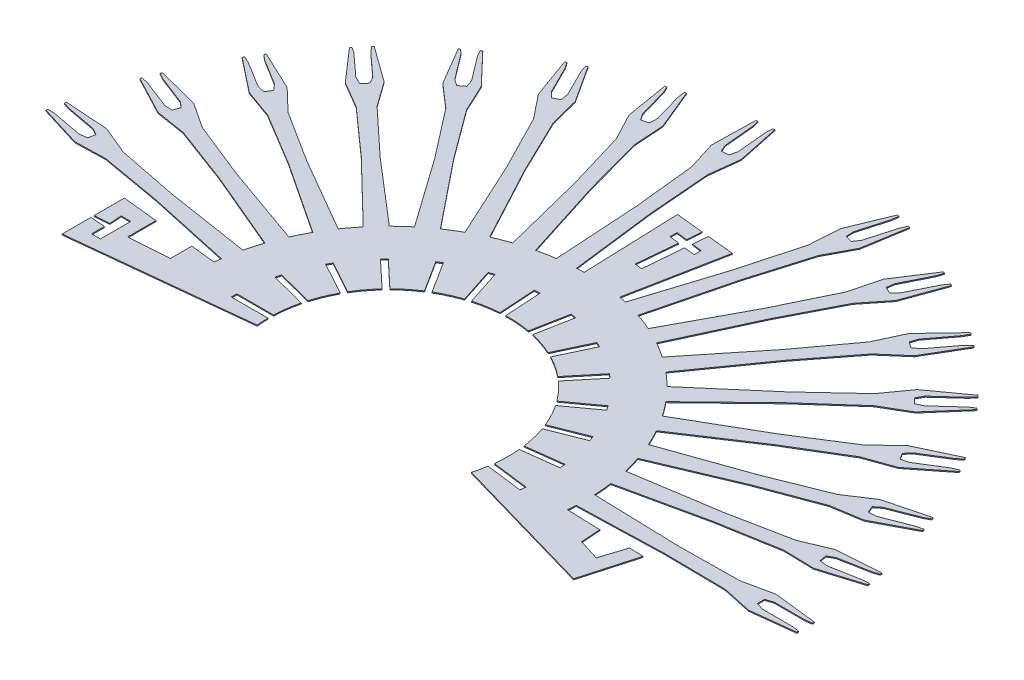
SolidWorks part; units mm, degrees
ref_plane "Front Plane" through (0, 0, 0) normal (0, 0, 1) x (1, 0, 0)
ref_plane "Top Plane" through (0, 0, 0) normal (0, 1, 0) x (1, 0, 0)
ref_plane "Right Plane" through (0, 0, 0) normal (1, 0, 0) x (0, 0, -1)
sketch "Sketch1" plane through (0, 0, 0) normal (0, 1, 0) x (1, 0, 0)
  line L5558 (72.849, 49.9) -> (72.743, 47.748) construction
  line L5559 (72.743, 47.748) -> (72.425, 45.667) construction
  line L5560 (72.425, 45.667) -> (71.896, 43.656) construction
  line L5561 (71.896, 43.656) -> (71.208, 41.716) construction
  line L5562 (71.208, 41.716) -> (70.309, 39.899) construction
  line L5563 (70.309, 39.899) -> (69.286, 38.171) construction
  line L5564 (69.286, 38.171) -> (66.71, 35.048) construction
  line L5565 (66.71, 35.048) -> (63.588, 32.491) construction
  line L5566 (63.588, 32.491) -> (61.877, 31.45) construction
  line L5567 (61.877, 31.45) -> (60.043, 30.551) construction
  line L5568 (60.043, 30.551) -> (58.12, 29.863) construction
  line L5569 (58.12, 29.863) -> (56.109, 29.333) construction
  line L5570 (56.109, 29.333) -> (54.01, 29.016) construction
  line L5571 (54.01, 29.016) -> (51.876, 28.91) construction
  line L5572 (51.876, 28.91) -> (49.724, 29.016) construction
  line L5573 (49.724, 29.016) -> (47.643, 29.333) construction
  line L5574 (47.643, 29.333) -> (45.632, 29.863) construction
  line L5575 (45.632, 29.863) -> (43.692, 30.551) construction
  line L5576 (43.692, 30.551) -> (41.839, 31.45) construction
  line L5577 (41.839, 31.45) -> (40.128, 32.491) construction
  line L5578 (40.128, 32.491) -> (37.006, 35.048) construction
  line L5579 (37.006, 35.048) -> (34.431, 38.171) construction
  line L5580 (34.431, 38.171) -> (33.408, 39.899) construction
  line L5581 (33.408, 39.899) -> (32.508, 41.716) construction
  line L5582 (32.508, 41.716) -> (31.821, 43.656) construction
  line L5583 (31.821, 43.656) -> (31.291, 45.667) construction
  line L5584 (31.291, 45.667) -> (30.974, 47.748) construction
  line L5585 (30.974, 47.748) -> (30.868, 49.9) construction
  line L5586 (30.868, 49.9) -> (30.974, 52.035) construction
  line L5587 (30.974, 52.035) -> (31.291, 54.134) construction
  line L5588 (31.291, 54.134) -> (31.821, 56.145) construction
  line L5589 (31.821, 56.145) -> (32.508, 58.067) construction
  line L5590 (32.508, 58.067) -> (33.408, 59.919) construction
  line L5591 (33.408, 59.919) -> (34.431, 61.648) construction
  line L5592 (34.431, 61.648) -> (37.006, 64.77) construction
  line L5593 (37.006, 64.77) -> (40.128, 67.328) construction
  line L5594 (40.128, 67.328) -> (41.839, 68.368) construction
  line L5595 (41.839, 68.368) -> (43.692, 69.268) construction
  line L5596 (43.692, 69.268) -> (45.632, 69.956) construction
  line L5597 (45.632, 69.956) -> (47.643, 70.485) construction
  line L5598 (47.643, 70.485) -> (49.724, 70.803) construction
  line L5599 (49.724, 70.803) -> (51.876, 70.908) construction
  line L5600 (51.876, 70.908) -> (54.01, 70.803) construction
  line L5601 (54.01, 70.803) -> (56.109, 70.485) construction
  line L5602 (56.109, 70.485) -> (58.12, 69.956) construction
  line L5603 (58.12, 69.956) -> (60.043, 69.268) construction
  line L5604 (60.043, 69.268) -> (61.877, 68.368) construction
  line L5605 (61.877, 68.368) -> (63.588, 67.328) construction
  line L5606 (63.588, 67.328) -> (66.71, 64.77) construction
  line L5607 (66.71, 64.77) -> (69.286, 61.648) construction
  line L5608 (69.286, 61.648) -> (70.309, 59.919) construction
  line L5609 (70.309, 59.919) -> (71.208, 58.067) construction
  line L5610 (71.208, 58.067) -> (71.896, 56.145) construction
  line L5611 (71.896, 56.145) -> (72.425, 54.134) construction
  line L5612 (72.425, 54.134) -> (72.743, 52.035) construction
  line L5613 (72.743, 52.035) -> (72.849, 49.9) construction
  line L5614 (62.054, 49.9) -> (61.842, 47.854) construction
  line L5615 (61.842, 47.854) -> (61.26, 45.932) construction
  line L5616 (61.26, 45.932) -> (60.307, 44.203) construction
  line L5617 (60.307, 44.203) -> (59.055, 42.704) construction
  line L5618 (59.055, 42.704) -> (57.556, 41.451) construction
  line L5619 (57.556, 41.451) -> (55.827, 40.499) construction
  line L5620 (55.827, 40.499) -> (53.922, 39.917) construction
  line L5621 (53.922, 39.917) -> (51.858, 39.705) construction
  line L5622 (51.858, 39.705) -> (49.795, 39.917) construction
  line L5623 (49.795, 39.917) -> (47.89, 40.499) construction
  line L5624 (47.89, 40.499) -> (46.143, 41.451) construction
  line L5625 (46.143, 41.451) -> (44.644, 42.704) construction
  line L5626 (44.644, 42.704) -> (43.392, 44.203) construction
  line L5627 (43.392, 44.203) -> (42.439, 45.932) construction
  line L5628 (42.439, 45.932) -> (41.857, 47.854) construction
  line L5629 (41.857, 47.854) -> (41.645, 49.9) construction
  line L5630 (41.645, 49.9) -> (41.857, 51.964) construction
  line L5631 (41.857, 51.964) -> (42.439, 53.869) construction
  line L5632 (42.439, 53.869) -> (43.392, 55.615) construction
  line L5633 (43.392, 55.615) -> (44.644, 57.115) construction
  line L5634 (44.644, 57.115) -> (46.143, 58.367) construction
  line L5635 (46.143, 58.367) -> (47.89, 59.32) construction
  line L5636 (47.89, 59.32) -> (49.795, 59.902) construction
  line L5637 (49.795, 59.902) -> (51.858, 60.113) construction
  line L5638 (51.858, 60.113) -> (53.922, 59.902) construction
  line L5639 (53.922, 59.902) -> (55.827, 59.32) construction
  line L5640 (55.827, 59.32) -> (57.556, 58.367) construction
  line L5641 (57.556, 58.367) -> (59.055, 57.115) construction
  line L5642 (59.055, 57.115) -> (60.307, 55.615) construction
  line L5643 (60.307, 55.615) -> (61.26, 53.869) construction
  line L5644 (61.26, 53.869) -> (61.842, 51.964) construction
  line L5645 (61.842, 51.964) -> (62.054, 49.9) construction
  line L5646 (30.85, 49.9) -> (51.841, 49.9) construction
  line L5647 (53.675, 70.82) -> (51.841, 49.9) construction
  line L5648 (72.531, 46.249) -> (51.858, 49.9) construction
  line L5649 (72.796, 48.436) -> (51.841, 49.9) construction
  line L5650 (51.488, 70.891) -> (51.841, 49.9) construction
  line L5651 (55.862, 70.52) -> (51.858, 49.9) construction
  line L5652 (30.956, 47.696) -> (51.841, 49.9) construction
  line L5653 (30.956, 52.088) -> (51.841, 49.9) construction
  line L5654 (72.037, 44.115) -> (51.841, 49.9) construction
  line L5655 (62.406, 49.177) -> (67.045, 49.424) construction
  line L5656 (67.345, 50.077) -> (67.469, 50.324) construction
  line L5657 (67.469, 50.324) -> (67.68, 50.377) construction
  line L5658 (67.68, 50.377) -> (67.892, 50.271) construction
  line L5659 (67.892, 50.271) -> (67.945, 50.059) construction
  line L5660 (67.945, 50.059) -> (67.839, 49.848) construction
  line L5661 (67.839, 49.848) -> (67.628, 49.759) construction
  line L5662 (67.628, 49.759) -> (67.416, 49.865) construction
  line L5663 (67.416, 49.865) -> (67.345, 50.077) construction
  line L5664 (69.832, 50.094) -> (69.938, 50.341) construction
  line L5665 (69.938, 50.341) -> (70.168, 50.394) construction
  line L5666 (70.168, 50.394) -> (70.379, 50.288) construction
  line L5667 (70.379, 50.288) -> (70.432, 50.077) construction
  line L5668 (70.432, 50.077) -> (70.326, 49.865) construction
  line L5669 (70.326, 49.865) -> (70.115, 49.777) construction
  line L5670 (70.115, 49.777) -> (69.903, 49.883) construction
  line L5671 (69.903, 49.883) -> (69.832, 50.094) construction
  line L5672 (67.045, 49.424) -> (71.702, 49.477) construction
  line L5673 (71.914, 50.094) -> (71.702, 49.477) construction
  line L5674 (62.389, 50.835) -> (67.045, 50.659) construction
  line L5675 (67.045, 50.659) -> (71.702, 50.712) construction
  line L5676 (71.914, 50.094) -> (71.702, 50.712) construction
  line L5677 (70.132, 50.377) -> (67.645, 50.359) construction
  line L5678 (70.15, 49.777) -> (67.645, 49.742) construction
  line L5679 (57.344, 49.953) -> (51.841, 49.9) construction
  line L5680 (62.353, 51.118) -> (66.887, 52.229) construction
  line L5681 (67.045, 52.917) -> (67.345, 53.252) construction
  line L5682 (67.345, 53.252) -> (67.557, 53.199) construction
  line L5683 (67.557, 53.199) -> (67.663, 52.987) construction
  line L5684 (67.663, 52.987) -> (67.61, 52.776) construction
  line L5685 (67.61, 52.776) -> (67.398, 52.652) construction
  line L5686 (67.398, 52.652) -> (67.187, 52.723) construction
  line L5687 (67.187, 52.723) -> (67.045, 52.917) construction
  line L5688 (69.48, 53.393) -> (69.779, 53.746) construction
  line L5689 (69.779, 53.746) -> (69.991, 53.693) construction
  line L5690 (69.991, 53.693) -> (70.097, 53.481) construction
  line L5691 (70.097, 53.481) -> (70.044, 53.269) construction
  line L5692 (70.044, 53.269) -> (69.832, 53.128) construction
  line L5693 (69.832, 53.128) -> (69.621, 53.217) construction
  line L5694 (69.621, 53.217) -> (69.48, 53.393) construction
  line L5695 (66.887, 52.229) -> (71.455, 53.128) construction
  line L5696 (71.543, 53.763) -> (71.455, 53.128) construction
  line L5697 (62.036, 52.758) -> (66.64, 53.428) construction
  line L5698 (66.64, 53.428) -> (71.208, 54.328) construction
  line L5699 (71.543, 53.781) -> (71.208, 54.328) construction
  line L5700 (69.744, 53.728) -> (67.292, 53.252) construction
  line L5701 (69.85, 53.128) -> (67.416, 52.634) construction
  line L5702 (57.238, 50.959) -> (51.841, 49.9) construction
  line L5703 (61.965, 53.023) -> (66.199, 54.945) construction
  line L5704 (66.234, 55.651) -> (66.446, 56.039) construction
  line L5705 (66.446, 56.039) -> (66.693, 56.021) construction
  line L5706 (66.693, 56.021) -> (66.851, 55.827) construction
  line L5707 (66.851, 55.827) -> (66.64, 55.457) construction
  line L5708 (66.64, 55.457) -> (66.393, 55.492) construction
  line L5709 (66.393, 55.492) -> (66.234, 55.651) construction
  line L5710 (68.545, 56.568) -> (68.756, 56.956) construction
  line L5711 (68.756, 56.956) -> (69.003, 56.938) construction
  line L5712 (69.003, 56.938) -> (69.162, 56.744) construction
  line L5713 (69.162, 56.744) -> (68.95, 56.374) construction
  line L5714 (68.95, 56.374) -> (68.703, 56.409) construction
  line L5715 (68.703, 56.409) -> (68.545, 56.568) construction
  line L5716 (66.199, 54.945) -> (70.52, 56.656) construction
  line L5717 (70.503, 57.309) -> (70.52, 56.656) construction
  line L5718 (61.348, 54.575) -> (65.74, 56.092) construction
  line L5719 (65.74, 56.092) -> (70.079, 57.803) construction
  line L5720 (70.503, 57.309) -> (70.079, 57.803) construction
  line L5721 (68.739, 56.938) -> (66.41, 56.021) construction
  line L5722 (68.968, 56.374) -> (66.64, 55.439) construction
  line L5723 (56.956, 51.929) -> (51.841, 49.9) construction
  line L5724 (61.225, 54.822) -> (65.035, 57.485) construction
  line L5725 (64.946, 58.191) -> (65.07, 58.614) construction
  line L5726 (65.07, 58.614) -> (65.317, 58.632) construction
  line L5727 (65.317, 58.632) -> (65.493, 58.473) construction
  line L5728 (65.493, 58.473) -> (65.528, 58.244) construction
  line L5729 (65.528, 58.244) -> (65.37, 58.05) construction
  line L5730 (65.37, 58.05) -> (64.946, 58.191) construction
  line L5731 (67.045, 59.514) -> (67.169, 59.937) construction
  line L5732 (67.169, 59.937) -> (67.416, 59.955) construction
  line L5733 (67.416, 59.955) -> (67.592, 59.796) construction
  line L5734 (67.592, 59.796) -> (67.628, 59.567) construction
  line L5735 (67.628, 59.567) -> (67.469, 59.373) construction
  line L5736 (67.469, 59.373) -> (67.045, 59.514) construction
  line L5737 (65.035, 57.485) -> (68.968, 59.972) construction
  line L5738 (68.827, 60.607) -> (68.968, 59.972) construction
  line L5739 (60.325, 56.233) -> (64.382, 58.526) construction
  line L5740 (64.382, 58.526) -> (68.315, 61.013) construction
  line L5741 (68.827, 60.607) -> (68.315, 61.013) construction
  line L5742 (67.169, 59.919) -> (65.052, 58.579) construction
  line L5743 (67.486, 59.39) -> (65.37, 58.067) construction
  line L5744 (56.497, 52.828) -> (51.858, 49.9) construction
  line L5745 (60.149, 56.444) -> (63.429, 59.761) construction
  line L5746 (63.2, 60.448) -> (63.147, 60.678) construction
  line L5747 (63.147, 60.678) -> (63.288, 60.889) construction
  line L5748 (63.288, 60.889) -> (63.5, 60.942) construction
  line L5749 (63.5, 60.942) -> (63.712, 60.837) construction
  line L5750 (63.712, 60.837) -> (63.765, 60.607) construction
  line L5751 (63.765, 60.607) -> (63.659, 60.396) construction
  line L5752 (63.659, 60.396) -> (63.412, 60.343) construction
  line L5753 (63.412, 60.343) -> (63.2, 60.448) construction
  line L5754 (65.017, 62.124) -> (64.964, 62.371) construction
  line L5755 (64.964, 62.371) -> (65.105, 62.583) construction
  line L5756 (65.105, 62.583) -> (65.317, 62.636) construction
  line L5757 (65.317, 62.636) -> (65.528, 62.53) construction
  line L5758 (65.528, 62.53) -> (65.581, 62.283) construction
  line L5759 (65.581, 62.283) -> (65.476, 62.071) construction
  line L5760 (65.476, 62.071) -> (65.229, 62.018) construction
  line L5761 (65.229, 62.018) -> (65.017, 62.124) construction
  line L5762 (63.429, 59.761) -> (66.834, 62.936) construction
  line L5763 (66.587, 63.535) -> (66.834, 62.936) construction
  line L5764 (59.02, 57.679) -> (62.583, 60.678) construction
  line L5765 (62.583, 60.678) -> (66.005, 63.835) construction
  line L5766 (66.587, 63.535) -> (66.005, 63.835) construction
  line L5767 (65.07, 62.548) -> (63.235, 60.854) construction
  line L5768 (65.493, 62.089) -> (63.659, 60.396) construction
  line L5769 (55.88, 53.622) -> (51.841, 49.9) construction
  line L5770 (58.808, 57.873) -> (61.419, 61.718) construction
  line L5771 (61.083, 62.353) -> (60.995, 62.583) construction
  line L5772 (60.995, 62.583) -> (61.083, 62.794) construction
  line L5773 (61.083, 62.794) -> (61.295, 62.9) construction
  line L5774 (61.295, 62.9) -> (61.507, 62.83) construction
  line L5775 (61.507, 62.83) -> (61.613, 62.618) construction
  line L5776 (61.613, 62.618) -> (61.524, 62.371) construction
  line L5777 (61.524, 62.371) -> (61.313, 62.301) construction
  line L5778 (61.313, 62.301) -> (61.083, 62.353) construction
  line L5779 (62.565, 64.329) -> (62.477, 64.576) construction
  line L5780 (62.477, 64.576) -> (62.565, 64.788) construction
  line L5781 (62.565, 64.788) -> (62.777, 64.893) construction
  line L5782 (62.777, 64.893) -> (62.988, 64.805) construction
  line L5783 (62.988, 64.805) -> (63.094, 64.594) construction
  line L5784 (63.094, 64.594) -> (63.006, 64.364) construction
  line L5785 (63.006, 64.364) -> (62.794, 64.276) construction
  line L5786 (62.794, 64.276) -> (62.565, 64.329) construction
  line L5787 (61.419, 61.718) -> (64.206, 65.458) construction
  line L5788 (63.835, 66.005) -> (64.206, 65.458) construction
  line L5789 (57.485, 58.861) -> (60.431, 62.459) construction
  line L5790 (60.431, 62.459) -> (63.2, 66.199) construction
  line L5791 (63.835, 66.005) -> (63.2, 66.199) construction
  line L5792 (62.53, 64.752) -> (61.031, 62.759) construction
  line L5793 (63.024, 64.382) -> (61.524, 62.389) construction
  line L5794 (55.122, 54.31) -> (51.858, 49.9) construction
  line L5795 (57.238, 59.002) -> (59.09, 63.271) construction
  line L5796 (58.649, 63.835) -> (58.508, 64.047) construction
  line L5797 (58.508, 64.047) -> (58.561, 64.258) construction
  line L5798 (58.561, 64.258) -> (58.755, 64.417) construction
  line L5799 (58.755, 64.417) -> (58.967, 64.364) construction
  line L5800 (58.967, 64.364) -> (59.126, 64.17) construction
  line L5801 (59.126, 64.17) -> (59.073, 63.941) construction
  line L5802 (59.073, 63.941) -> (58.879, 63.8) construction
  line L5803 (58.879, 63.8) -> (58.649, 63.835) construction
  line L5804 (59.743, 66.058) -> (59.602, 66.269) construction
  line L5805 (59.602, 66.269) -> (59.655, 66.481) construction
  line L5806 (59.655, 66.481) -> (59.849, 66.604) construction
  line L5807 (59.849, 66.604) -> (60.06, 66.587) construction
  line L5808 (60.06, 66.587) -> (60.219, 66.393) construction
  line L5809 (60.219, 66.393) -> (60.166, 66.163) construction
  line L5810 (60.166, 66.163) -> (59.972, 66.022) construction
  line L5811 (59.972, 66.022) -> (59.743, 66.058) construction
  line L5812 (59.09, 63.271) -> (61.136, 67.451) construction
  line L5813 (60.695, 67.927) -> (61.136, 67.451) construction
  line L5814 (55.739, 59.743) -> (57.979, 63.818) construction
  line L5815 (57.979, 63.818) -> (60.025, 67.998) construction
  line L5816 (60.678, 67.927) -> (60.025, 67.998) construction
  line L5817 (59.619, 66.463) -> (58.526, 64.223) construction
  line L5818 (60.184, 66.181) -> (59.073, 63.941) construction
  line L5819 (54.257, 54.822) -> (51.841, 49.9) construction
  line L5820 (55.457, 59.849) -> (56.497, 64.382) construction
  line L5821 (55.951, 64.841) -> (55.792, 64.999) construction
  line L5822 (55.792, 64.999) -> (55.792, 65.246) construction
  line L5823 (55.792, 65.246) -> (55.951, 65.423) construction
  line L5824 (55.951, 65.423) -> (56.18, 65.423) construction
  line L5825 (56.18, 65.423) -> (56.339, 65.264) construction
  line L5826 (56.339, 65.264) -> (56.339, 65.035) construction
  line L5827 (56.339, 65.035) -> (56.18, 64.876) construction
  line L5828 (56.18, 64.876) -> (55.951, 64.841) construction
  line L5829 (56.603, 67.239) -> (56.444, 67.398) construction
  line L5830 (56.444, 67.398) -> (56.444, 67.628) construction
  line L5831 (56.444, 67.628) -> (56.603, 67.822) construction
  line L5832 (56.603, 67.822) -> (56.85, 67.822) construction
  line L5833 (56.85, 67.822) -> (57.009, 67.663) construction
  line L5834 (57.009, 67.663) -> (57.009, 67.416) construction
  line L5835 (57.009, 67.416) -> (56.85, 67.257) construction
  line L5836 (56.85, 67.257) -> (56.603, 67.239) construction
  line L5837 (56.497, 64.382) -> (57.732, 68.88) construction
  line L5838 (57.203, 69.25) -> (57.732, 68.88) construction
  line L5839 (53.852, 60.29) -> (55.298, 64.717) construction
  line L5840 (55.298, 64.717) -> (56.533, 69.197) construction
  line L5841 (57.185, 69.25) -> (56.533, 69.197) construction
  line L5842 (56.427, 67.61) -> (55.757, 65.211) construction
  line L5843 (57.009, 67.451) -> (56.356, 65.035) construction
  line L5844 (53.305, 55.192) -> (51.841, 49.9) construction
  line L5845 (51.664, 60.484) -> (50.994, 65.088) construction
  line L5846 (50.324, 65.317) -> (50.112, 65.423) construction
  line L5847 (50.112, 65.423) -> (50.024, 65.634) construction
  line L5848 (50.024, 65.634) -> (50.112, 65.846) construction
  line L5849 (50.112, 65.846) -> (50.324, 65.952) construction
  line L5850 (50.324, 65.952) -> (50.553, 65.846) construction
  line L5851 (50.553, 65.846) -> (50.641, 65.634) construction
  line L5852 (50.641, 65.634) -> (50.553, 65.423) construction
  line L5853 (50.553, 65.423) -> (50.324, 65.317) construction
  line L5854 (50.077, 67.786) -> (49.865, 67.892) construction
  line L5855 (49.865, 67.892) -> (49.795, 68.104) construction
  line L5856 (49.795, 68.104) -> (49.865, 68.315) construction
  line L5857 (49.865, 68.315) -> (50.077, 68.421) construction
  line L5858 (50.077, 68.421) -> (50.324, 68.315) construction
  line L5859 (50.324, 68.315) -> (50.394, 68.104) construction
  line L5860 (50.394, 68.104) -> (50.324, 67.892) construction
  line L5861 (50.324, 67.892) -> (50.077, 67.786) construction
  line L5862 (50.994, 65.088) -> (50.535, 69.727) construction
  line L5863 (49.918, 69.885) -> (50.535, 69.727) construction
  line L5864 (50.006, 60.325) -> (49.759, 64.964) construction
  line L5865 (49.759, 64.964) -> (49.318, 69.603) construction
  line L5866 (49.9, 69.885) -> (49.318, 69.603) construction
  line L5867 (49.777, 68.068) -> (50.024, 65.599) construction
  line L5868 (50.377, 68.139) -> (50.624, 65.652) construction
  line L5869 (51.312, 55.368) -> (51.858, 49.9) construction
  line L5870 (49.724, 60.272) -> (48.225, 64.664) construction
  line L5871 (47.519, 64.788) -> (47.308, 64.841) construction
  line L5872 (47.308, 64.841) -> (47.184, 65.052) construction
  line L5873 (47.184, 65.052) -> (47.237, 65.264) construction
  line L5874 (47.237, 65.264) -> (47.413, 65.387) construction
  line L5875 (47.413, 65.387) -> (47.66, 65.334) construction
  line L5876 (47.66, 65.334) -> (47.784, 65.158) construction
  line L5877 (47.784, 65.158) -> (47.731, 64.946) construction
  line L5878 (47.731, 64.946) -> (47.519, 64.788) construction
  line L5879 (46.831, 67.169) -> (46.62, 67.222) construction
  line L5880 (46.62, 67.222) -> (46.496, 67.433) construction
  line L5881 (46.496, 67.433) -> (46.549, 67.645) construction
  line L5882 (46.549, 67.645) -> (46.725, 67.769) construction
  line L5883 (46.725, 67.769) -> (46.972, 67.716) construction
  line L5884 (46.972, 67.716) -> (47.096, 67.539) construction
  line L5885 (47.096, 67.539) -> (47.043, 67.328) construction
  line L5886 (47.043, 67.328) -> (46.831, 67.169) construction
  line L5887 (48.225, 64.664) -> (46.937, 69.144) construction
  line L5888 (46.284, 69.18) -> (46.937, 69.144) construction
  line L5889 (48.119, 59.796) -> (47.043, 64.329) construction
  line L5890 (47.043, 64.329) -> (45.738, 68.809) construction
  line L5891 (46.267, 69.18) -> (45.738, 68.792) construction
  line L5892 (46.478, 67.381) -> (47.166, 64.982) construction
  line L5893 (47.061, 67.557) -> (47.766, 65.158) construction
  line L5894 (50.324, 55.174) -> (51.841, 49.9) construction
  line L5895 (47.854, 59.708) -> (45.579, 63.747) construction
  line L5896 (44.873, 63.729) -> (44.662, 63.765) construction
  line L5897 (44.662, 63.765) -> (44.503, 63.923) construction
  line L5898 (44.503, 63.923) -> (44.503, 64.153) construction
  line L5899 (44.503, 64.153) -> (44.662, 64.311) construction
  line L5900 (44.662, 64.311) -> (44.891, 64.311) construction
  line L5901 (44.891, 64.311) -> (45.05, 64.135) construction
  line L5902 (45.05, 64.135) -> (45.05, 63.923) construction
  line L5903 (45.05, 63.923) -> (44.873, 63.729) construction
  line L5904 (43.762, 65.952) -> (43.55, 65.969) construction
  line L5905 (43.55, 65.969) -> (43.356, 66.128) construction
  line L5906 (43.356, 66.128) -> (43.392, 66.375) construction
  line L5907 (43.392, 66.375) -> (43.55, 66.534) construction
  line L5908 (43.55, 66.534) -> (43.78, 66.534) construction
  line L5909 (43.78, 66.534) -> (43.938, 66.34) construction
  line L5910 (43.938, 66.34) -> (43.938, 66.128) construction
  line L5911 (43.938, 66.128) -> (43.762, 65.952) construction
  line L5912 (45.579, 63.747) -> (43.498, 67.91) construction
  line L5913 (42.845, 67.839) -> (43.498, 67.91) construction
  line L5914 (46.373, 58.949) -> (44.485, 63.2) construction
  line L5915 (44.485, 63.2) -> (42.386, 67.363) construction
  line L5916 (42.827, 67.839) -> (42.386, 67.363) construction
  line L5917 (43.374, 66.111) -> (44.485, 63.87) construction
  line L5918 (43.921, 66.393) -> (45.032, 64.153) construction
  line L5919 (49.389, 54.804) -> (51.841, 49.9) construction
  line L5920 (46.126, 58.808) -> (43.145, 62.371) construction
  line L5921 (42.457, 62.23) -> (42.245, 62.195) construction
  line L5922 (42.245, 62.195) -> (42.051, 62.336) construction
  line L5923 (42.051, 62.336) -> (41.998, 62.565) construction
  line L5924 (41.998, 62.565) -> (42.139, 62.759) construction
  line L5925 (42.139, 62.759) -> (42.369, 62.777) construction
  line L5926 (42.369, 62.777) -> (42.563, 62.653) construction
  line L5927 (42.563, 62.653) -> (42.58, 62.442) construction
  line L5928 (42.58, 62.442) -> (42.457, 62.23) construction
  line L5929 (40.958, 64.188) -> (40.746, 64.17) construction
  line L5930 (40.746, 64.17) -> (40.552, 64.294) construction
  line L5931 (40.552, 64.294) -> (40.499, 64.541) construction
  line L5932 (40.499, 64.541) -> (40.64, 64.717) construction
  line L5933 (40.64, 64.717) -> (40.869, 64.752) construction
  line L5934 (40.869, 64.752) -> (41.063, 64.611) construction
  line L5935 (41.063, 64.611) -> (41.081, 64.4) construction
  line L5936 (41.081, 64.4) -> (40.958, 64.188) construction
  line L5937 (43.145, 62.371) -> (40.323, 66.075) construction
  line L5938 (39.705, 65.881) -> (40.323, 66.075) construction
  line L5939 (44.803, 57.803) -> (42.157, 61.63) construction
  line L5940 (42.157, 61.63) -> (39.352, 65.334) construction
  line L5941 (39.705, 65.881) -> (39.352, 65.334) construction
  line L5942 (40.534, 64.276) -> (42.051, 62.301) construction
  line L5943 (41.028, 64.647) -> (42.545, 62.671) construction
  line L5944 (48.525, 54.275) -> (51.858, 49.9) construction
  line L5945 (44.591, 57.609) -> (41.01, 60.572) construction
  line L5946 (40.358, 60.29) -> (40.146, 60.219) construction
  line L5947 (40.146, 60.219) -> (39.934, 60.325) construction
  line L5948 (39.934, 60.325) -> (39.846, 60.537) construction
  line L5949 (39.846, 60.537) -> (39.952, 60.748) construction
  line L5950 (39.952, 60.748) -> (40.164, 60.819) construction
  line L5951 (40.164, 60.819) -> (40.375, 60.748) construction
  line L5952 (40.375, 60.748) -> (40.464, 60.537) construction
  line L5953 (40.464, 60.537) -> (40.358, 60.29) construction
  line L5954 (38.523, 61.965) -> (38.312, 61.877) construction
  line L5955 (38.312, 61.877) -> (38.1, 61.983) construction
  line L5956 (38.1, 61.983) -> (38.012, 62.195) construction
  line L5957 (38.012, 62.195) -> (38.118, 62.406) construction
  line L5958 (38.118, 62.406) -> (38.329, 62.495) construction
  line L5959 (38.329, 62.495) -> (38.541, 62.406) construction
  line L5960 (38.541, 62.406) -> (38.629, 62.195) construction
  line L5961 (38.629, 62.195) -> (38.523, 61.965) construction
  line L5962 (41.01, 60.572) -> (37.553, 63.694) construction
  line L5963 (36.989, 63.394) -> (37.553, 63.694) construction
  line L5964 (43.48, 56.374) -> (40.181, 59.655) construction
  line L5965 (40.181, 59.655) -> (36.724, 62.777) construction
  line L5966 (36.971, 63.377) -> (36.724, 62.777) construction
  line L5967 (38.1, 61.965) -> (39.952, 60.29) construction
  line L5968 (38.506, 62.424) -> (40.358, 60.748) construction
  line L5969 (47.784, 53.587) -> (51.841, 49.9) construction
  line L5970 (43.303, 56.145) -> (39.247, 58.402) construction
  line L5971 (38.647, 58.014) -> (38.453, 57.908) construction
  line L5972 (38.453, 57.908) -> (38.223, 57.961) construction
  line L5973 (38.223, 57.961) -> (38.118, 58.173) construction
  line L5974 (38.118, 58.173) -> (38.171, 58.385) construction
  line L5975 (38.171, 58.385) -> (38.594, 58.455) construction
  line L5976 (38.594, 58.455) -> (38.7, 58.244) construction
  line L5977 (38.7, 58.244) -> (38.647, 58.014) construction
  line L5978 (36.53, 59.32) -> (36.354, 59.214) construction
  line L5979 (36.354, 59.214) -> (36.107, 59.267) construction
  line L5980 (36.107, 59.267) -> (36.001, 59.478) construction
  line L5981 (36.001, 59.478) -> (36.054, 59.69) construction
  line L5982 (36.054, 59.69) -> (36.477, 59.761) construction
  line L5983 (36.477, 59.761) -> (36.583, 59.549) construction
  line L5984 (36.583, 59.549) -> (36.53, 59.32) construction
  line L5985 (39.247, 58.402) -> (35.278, 60.854) construction
  line L5986 (34.766, 60.448) -> (35.278, 60.837) construction
  line L5987 (42.439, 54.733) -> (38.594, 57.344) construction
  line L5988 (38.594, 57.344) -> (34.625, 59.796) construction
  line L5989 (34.766, 60.431) -> (34.625, 59.796) construction
  line L5990 (36.124, 59.249) -> (38.241, 57.926) construction
  line L5991 (36.442, 59.761) -> (38.559, 58.455) construction
  line L5992 (47.184, 52.776) -> (51.841, 49.9) construction
  line L5993 (42.316, 54.469) -> (37.888, 55.951) construction
  line L5994 (37.377, 55.457) -> (37.218, 55.316) construction
  line L5995 (37.218, 55.316) -> (36.989, 55.316) construction
  line L5996 (36.989, 55.316) -> (36.83, 55.51) construction
  line L5997 (36.83, 55.51) -> (36.848, 55.739) construction
  line L5998 (36.848, 55.739) -> (37.006, 55.898) construction
  line L5999 (37.006, 55.898) -> (37.253, 55.88) construction
  line L6000 (37.253, 55.88) -> (37.412, 55.686) construction
  line L6001 (37.412, 55.686) -> (37.377, 55.457) construction
  line L6002 (35.066, 56.356) -> (34.907, 56.215) construction
  line L6003 (34.907, 56.215) -> (34.678, 56.215) construction
  line L6004 (34.678, 56.215) -> (34.519, 56.409) construction
  line L6005 (34.519, 56.409) -> (34.537, 56.638) construction
  line L6006 (34.537, 56.638) -> (34.696, 56.797) construction
  line L6007 (34.696, 56.797) -> (34.943, 56.78) construction
  line L6008 (34.943, 56.78) -> (35.101, 56.586) construction
  line L6009 (35.101, 56.586) -> (35.066, 56.356) construction
  line L6010 (37.888, 55.951) -> (33.549, 57.626) construction
  line L6011 (33.126, 57.132) -> (33.549, 57.626) construction
  line L6012 (41.716, 52.917) -> (37.447, 54.804) construction
  line L6013 (37.447, 54.804) -> (33.108, 56.48) construction
  line L6014 (33.126, 57.132) -> (33.108, 56.48) construction
  line L6015 (34.678, 56.198) -> (37.006, 55.298) construction
  line L6016 (34.89, 56.78) -> (37.218, 55.88) construction
  line L6017 (46.725, 51.876) -> (51.858, 49.9) construction
  line L6018 (41.628, 52.652) -> (37.024, 53.287) construction
  line L6019 (36.601, 52.705) -> (36.477, 52.529) construction
  line L6020 (36.477, 52.529) -> (36.23, 52.493) construction
  line L6021 (36.23, 52.493) -> (36.054, 52.652) construction
  line L6022 (36.054, 52.652) -> (36.019, 52.899) construction
  line L6023 (36.019, 52.899) -> (36.389, 53.111) construction
  line L6024 (36.389, 53.111) -> (36.583, 52.952) construction
  line L6025 (36.583, 52.952) -> (36.601, 52.705) construction
  line L6026 (34.167, 53.164) -> (34.043, 52.987) construction
  line L6027 (34.043, 52.987) -> (33.796, 52.952) construction
  line L6028 (33.796, 52.952) -> (33.62, 53.111) construction
  line L6029 (33.62, 53.111) -> (33.584, 53.358) construction
  line L6030 (33.584, 53.358) -> (33.955, 53.569) construction
  line L6031 (33.955, 53.569) -> (34.149, 53.411) construction
  line L6032 (34.149, 53.411) -> (34.167, 53.164) construction
  line L6033 (37.024, 53.287) -> (32.438, 54.134) construction
  line L6034 (32.12, 53.587) -> (32.438, 54.134) construction
  line L6035 (41.328, 51.012) -> (36.795, 52.07) construction
  line L6036 (36.795, 52.07) -> (32.226, 52.934) construction
  line L6037 (32.12, 53.569) -> (32.226, 52.934) construction
  line L6038 (33.814, 52.952) -> (36.266, 52.493) construction
  line L6039 (33.92, 53.552) -> (36.371, 53.093) construction
  line L6040 (46.461, 50.906) -> (51.858, 49.9) construction
  line L6041 (57.856, 49.9) -> (57.714, 48.683) construction
  line L6042 (57.714, 48.683) -> (57.379, 47.572) construction
  line L6043 (57.379, 47.572) -> (56.815, 46.567) construction
  line L6044 (56.815, 46.567) -> (56.109, 45.667) construction
  line L6045 (56.109, 45.667) -> (55.21, 44.944) construction
  line L6046 (55.21, 44.944) -> (54.204, 44.397) construction
  line L6047 (54.204, 44.397) -> (53.093, 44.044) construction
  line L6048 (53.093, 44.044) -> (51.876, 43.921) construction
  line L6049 (51.876, 43.921) -> (50.659, 44.044) construction
  line L6050 (50.659, 44.044) -> (49.512, 44.397) construction
  line L6051 (49.512, 44.397) -> (48.507, 44.944) construction
  line L6052 (48.507, 44.944) -> (47.607, 45.667) construction
  line L6053 (47.607, 45.667) -> (46.902, 46.567) construction
  line L6054 (46.902, 46.567) -> (46.337, 47.572) construction
  line L6055 (46.337, 47.572) -> (46.002, 48.683) construction
  line L6056 (46.002, 48.683) -> (45.861, 49.9) construction
  line L6057 (45.861, 49.9) -> (46.002, 51.118) construction
  line L6058 (46.002, 51.118) -> (46.337, 52.246) construction
  line L6059 (46.337, 52.246) -> (46.902, 53.252) construction
  line L6060 (46.902, 53.252) -> (47.607, 54.151) construction
  line L6061 (47.607, 54.151) -> (48.507, 54.875) construction
  line L6062 (48.507, 54.875) -> (49.512, 55.421) construction
  line L6063 (49.512, 55.421) -> (50.659, 55.774) construction
  line L6064 (50.659, 55.774) -> (51.876, 55.898) construction
  line L6065 (51.876, 55.898) -> (53.093, 55.774) construction
  line L6066 (53.093, 55.774) -> (54.204, 55.421) construction
  line L6067 (54.204, 55.421) -> (55.21, 54.875) construction
  line L6068 (55.21, 54.875) -> (56.109, 54.151) construction
  line L6069 (56.109, 54.151) -> (56.815, 53.252) construction
  line L6070 (56.815, 53.252) -> (57.379, 52.246) construction
  line L6071 (57.379, 52.246) -> (57.714, 51.118) construction
  line L6072 (57.714, 51.118) -> (57.856, 49.9) construction
sketch "Sketch2" plane through (0, 0, 0) normal (0, 1, 0) x (1, 0, 0)
  line L0 (41.7366, 50.9583) -> (36.5552, 51.5014)
  line L1 (51.841, 49.9) -> (53.163, 64.9033) construction
  line L2 (30.956, 52.088) -> (51.841, 49.9) construction
  line L3 (36.5552, 51.5014) -> (36.5552, 48.2869)
  line L4 (30.956, 47.696) -> (51.841, 49.9) construction
  line L5 (36.5552, 48.2869) -> (41.7327, 48.8337)
  line L7 (61.6124, 47.1011) -> (66.5007, 45.7008)
  line L8 (72.037, 44.115) -> (51.841, 49.9) construction
  line L9 (66.5007, 45.7008) -> (67.012, 48.8401)
  line L10 (72.796, 48.436) -> (51.841, 49.9) construction
  line L11 (67.012, 48.8401) -> (61.9609, 49.0012)
  line L12 (62.054, 49.9) -> (61.842, 47.854) construction
  line L13 (51.765, 60.0594) -> (51.586, 65.0642)
  line L14 (51.488, 70.891) -> (51.841, 49.9) construction
  line L15 (51.586, 65.0642) -> (54.7401, 64.7424)
  line L16 (55.862, 70.52) -> (51.858, 49.9) construction
  line L17 (54.7401, 64.7424) -> (53.794, 59.8702)
  circle A0 centre (51.841, 49.9) radius 6.2002
  arc A1 (61.9609, 49.0012) -> (53.794, 59.8702) centre (51.841, 49.9) ccw
  arc A2 (41.7375, 50.967) -> (41.7366, 50.9583) centre (51.841, 49.9) ccw
  arc A3 (41.7327, 48.8337) -> (41.7338, 48.8238) centre (51.841, 49.9) ccw
  arc A4 (41.7338, 48.8238) -> (61.6124, 47.1011) centre (51.841, 49.9) ccw
  arc A5 (51.765, 60.0594) -> (41.7375, 50.967) centre (51.841, 49.9) ccw
extrude "Boss-Extrude1" add sketch "Sketch2" along normal blind 0.05
sketch "Sketch3" plane through (0, 0, 0) normal (0, 1, 0) x (1, 0, 0)
  line L0 (34.2118, 50.4323) -> (32.9093, 50.6404) construction
  line L1 (30.85, 49.9) -> (51.841, 49.9) construction
  line L2 (41.7282, 50.4911) -> (37.2554, 50.3818) construction
  line L3 (32.9093, 50.6404) -> (30.8099, 50.6404) construction
  line L4 (30.8099, 50.6404) -> (30.3951, 50.6098) construction
  line L5 (30.3951, 50.6098) -> (30.1967, 50.3818) construction
  line L6 (32.1942, 50.0581) -> (31.3331, 50.0581) construction
  line L7 (37.2554, 50.3818) -> (34.2118, 50.4323) construction
  line L8 (31.0996, 50.116) -> (31.0522, 50.1661) construction
  line L9 (30.7793, 50.1661) -> (31.0522, 50.1661) construction
  line L10 (32.1963, 49.7413) -> (31.4424, 49.7413) construction
  line L11 (41.7282, 50.4911) -> (41.7282, 49.4512) construction
  line L12 (31.194, 49.6753) -> (31.1199, 49.6329) construction
  line L13 (30.7793, 50.1661) -> (30.7516, 50.116) construction
  line L14 (30.7516, 50.116) -> (30.1967, 50.1553) construction
  line L15 (30.7788, 49.6329) -> (31.1199, 49.6329) construction
  line L16 (30.1967, 50.1553) -> (30.1967, 50.3818) construction
  line L17 (30.3951, 49.2413) -> (30.1967, 49.4512) construction
  line L18 (30.8191, 49.1966) -> (30.3951, 49.2413) construction
  line L19 (32.6688, 49.1966) -> (30.8191, 49.1966) construction
  line L20 (41.7282, 49.4512) -> (37.2554, 49.5186) construction
  line L21 (34.213, 49.341) -> (32.6688, 49.1966) construction
  line L22 (30.7788, 49.6329) -> (30.7516, 49.685) construction
  line L23 (30.7516, 49.685) -> (30.1967, 49.6405) construction
  line L24 (30.1967, 49.6405) -> (30.1967, 49.4512) construction
  line L25 (37.2554, 49.5186) -> (34.213, 49.341) construction
  line L26 (51.841, 49.9) -> (28.9127, 49.9) construction
  line L27 (32.2385, 50.21) -> (30.6564, 50.21)
  line L28 (30.3129, 50.2585) -> (30.3129, 50.3538)
  line L29 (30.3129, 50.3538) -> (32.5485, 50.6098)
  line L30 (32.5485, 50.6098) -> (34.0857, 50.2819)
  line L31 (34.0857, 50.2819) -> (37.2554, 50.2437)
  line L32 (37.2554, 50.2437) -> (41.8575, 50.3818)
  line L33 (41.8575, 50.3818) -> (41.8575, 49.4182)
  line L34 (32.2385, 50.21) -> (32.6151, 50.0861)
  line L35 (32.6151, 50.0861) -> (32.6151, 49.7139)
  line L36 (30.6564, 50.21) -> (30.3129, 50.2585)
  line L37 (37.2554, 49.5563) -> (41.8575, 49.4182)
  line L38 (34.0857, 49.5181) -> (37.2554, 49.5563)
  line L39 (32.5485, 49.1902) -> (34.0857, 49.5181)
  line L40 (30.3129, 49.4462) -> (32.5485, 49.1902)
  line L41 (30.6564, 49.59) -> (30.3129, 49.5415)
  line L42 (30.3129, 49.5415) -> (30.3129, 49.4462)
  line L43 (32.2385, 49.59) -> (30.6564, 49.59)
  line L44 (32.2385, 49.59) -> (32.6151, 49.7139)
  circle A0 centre (32.2385, 49.7358) radius 0.1651 construction
  circle A1 centre (30.7793, 50.1661) radius 0.1651 construction
  circle A2 centre (32.2385, 49.9) radius 0.31 construction
  circle A3 centre (32.2385, 50.0642) radius 0.1651 construction
  circle A4 centre (35.387, 50.2437) radius 0.1651 construction
  arc A5 (31.3331, 50.0581) -> (31.0996, 50.116) centre (31.3331, 50.5581) cw construction
  arc A6 (32.1963, 49.7413) -> (32.1942, 50.0581) centre (32.2385, 49.9) ccw construction
  arc A7 (31.4424, 49.7413) -> (31.194, 49.6753) centre (31.4424, 49.2413) ccw construction
  circle A8 centre (32.2385, 50.3818) radius 0.1651 construction
  point P21 (41.7282, 49.9)
  point P54 (41.7282, 49.9)
  point P60 (41.8575, 49.9)
  point P68 (32.6151, 49.9)
extrude "Boss-Extrude2" add sketch "Sketch3" along normal blind 0.05
sketch "Sketch5" plane through (0, 0, 0) normal (0, 1, 0) x (1, 0, 0)
  line L0 (51.841, 49.9) -> (51.841, 47.986)
  line L1 (30.85, 49.9) -> (51.841, 49.9) construction
  line L2 (51.841, 49.9) -> (47.5187, 49.9)
  line L4 (47.5187, 49.9) -> (51.841, 47.986)
extrude "Boss-Extrude3" add sketch "Sketch5" along normal blind 0.05 separate body
pattern_circular "CirPattern1" count 18 over 180 about axis through (51.841, 0, -49.9) along (0, 1, 0) of "Boss-Extrude2"
sketch "Sketch8" plane through (0, 0, 0) normal (0, 1, 0) x (1, 0, 0)
  line L0 (36.5552, 48.2869) -> (27.9956, 47.1697)
  line L1 (27.9956, 47.1697) -> (27.9956, 52.8907)
  line L2 (27.9956, 52.8907) -> (36.5552, 51.5014)
  line L3 (36.5552, 51.5014) -> (36.5552, 48.754)
  line L5 (36.5552, 48.754) -> (36.5552, 48.2869)
  line L6 (51.6556, 72.5266) -> (51.586, 65.0642)
  line L7 (51.586, 65.0642) -> (54.7401, 64.7424)
  line L8 (54.7401, 64.7424) -> (56.407, 72.5266)
  line L9 (56.407, 72.5266) -> (51.6556, 72.5266)
  line L10 (47.955, 51.5014) -> (46.9983, 48.798)
  line L11 (46.9983, 48.798) -> (52.8392, 46.1614)
  line L12 (52.8392, 46.1614) -> (54.7401, 51.7191)
  line L13 (56.497, 52.828) -> (51.858, 49.9) construction
  line L14 (54.7401, 51.7191) -> (47.955, 51.5014)
extrude "Cut-Extrude4" cut sketch "Sketch8" against normal blind 0.05 and the other way through all
sketch "Sketch9" plane through (0, 0, 0) normal (0, 1, 0) x (1, 0, 0)
  line L0 (36.5552, 48.2869) -> (47.0091, 49.3901)
  line L1 (51.841, 49.9) -> (66.5007, 45.7008)
  line L2 (66.5007, 45.7008) -> (51.841, 34.8579)
  line L3 (51.841, 34.8579) -> (36.5552, 48.2869)
  line L4 (47.0091, 49.3901) -> (47.588, 50.4909)
  line L5 (47.588, 50.4909) -> (51.841, 49.9)
extrude "Cut-Extrude6" cut sketch "Sketch9" against normal blind 0.05 and the other way through all
sketch "Sketch12" plane through (0, 0, 0) normal (0, 1, 0) x (1, 0, 0)
  line L0 (36.5552, 51.5014) -> (38.3774, 51.5014)
  line L1 (38.3774, 51.5014) -> (38.3774, 49.8464)
  line L2 (38.3774, 49.8464) -> (40.4501, 49.9851)
  line L3 (40.4501, 49.9851) -> (40.4501, 51.1692)
  line L4 (40.4501, 51.1692) -> (37.3172, 51.7206)
  line L5 (37.3172, 51.7206) -> (36.5552, 51.5014)
  line L6 (66.0368, 49.0067) -> (65.0952, 45.6712)
  line L7 (53.0825, 66.1281) -> (52.9481, 64.1718)
  line L8 (67.012, 48.8401) -> (61.9609, 49.0012) construction
  line L9 (65.2739, 48.8955) -> (64.8588, 47.5883)
  line L10 (64.8588, 47.5883) -> (63.7611, 47.9369)
  line L11 (63.7611, 47.9369) -> (63.678, 49.0649)
  line L12 (63.678, 49.0649) -> (65.5048, 49.0067)
  line L13 (65.5048, 49.0067) -> (65.2739, 48.8955)
  line L14 (65.0952, 45.6712) -> (66.9581, 45.1452)
  line L15 (35.4312, 49.8586) -> (37.3125, 49.9972)
  line L16 (37.3125, 49.9972) -> (37.2663, 50.6247)
  line L17 (37.2663, 50.6247) -> (37.7661, 50.6247)
  line L18 (37.7661, 50.6247) -> (37.7661, 49.0512)
  line L19 (37.7661, 49.0512) -> (37.3125, 49.0512)
  line L20 (37.3125, 49.0512) -> (37.3125, 49.7158)
  line L21 (37.3125, 49.7158) -> (35.4312, 49.8586)
  line L22 (66.9581, 45.1452) -> (67.4623, 48.8914)
  line L23 (67.4623, 48.8914) -> (66.0368, 49.0067)
  line L24 (52.9481, 64.1718) -> (52.3858, 64.243)
  line L25 (52.3858, 64.243) -> (52.3858, 63.8789)
  line L26 (52.3858, 63.8789) -> (52.896, 63.8143)
  line L27 (53.8144, 63.698) -> (53.8144, 64.0546)
  line L28 (53.8144, 64.0546) -> (53.3003, 64.1253)
  line L29 (53.3003, 64.1253) -> (53.4738, 66.0149)
  line L30 (52.896, 63.8143) -> (52.7084, 61.7546)
  line L31 (53.2624, 63.7552) -> (53.8144, 63.698)
  line L32 (52.7084, 61.7546) -> (53.0877, 61.7007)
  line L33 (53.0877, 61.7007) -> (53.2624, 63.7552)
  line L34 (51.841, 49.9) -> (53.5625, 69.0822) construction
  line L35 (53.4738, 66.0149) -> (53.0825, 66.1281)
  circle A0 centre (0, 0) radius 0.1651 construction
  circle A1 centre (52.4536, 66.1109) radius 0.1651 construction
extrude "Cut-Extrude13" cut sketch "Sketch12" along normal blind 10
sketch "Sketch13" plane through (0, 0, 0) normal (0, 1, 0) x (1, 0, 0)
  line L0 (49.3736, 50.47) -> (43.9869, 51.853)
  line L1 (49.3092, 49.8384) -> (43.7478, 49.8384)
  line L2 (49.3092, 49.8384) -> (49.3092, 50.1245)
  line L3 (49.3092, 50.1245) -> (43.7478, 50.1245)
  line L4 (43.7478, 49.8384) -> (43.7478, 50.1245)
  line L5 (49.3736, 50.47) -> (49.4447, 50.7471)
  line L6 (49.4447, 50.7471) -> (44.058, 52.1302)
  line L7 (43.9869, 51.853) -> (44.058, 52.1302)
  line L8 (49.593, 51.0657) -> (44.7195, 53.7449)
  line L9 (49.593, 51.0657) -> (49.7308, 51.3164)
  line L10 (49.7308, 51.3164) -> (44.8573, 53.9956)
  line L11 (44.7195, 53.7449) -> (44.8573, 53.9956)
  line L12 (49.9537, 51.5881) -> (45.8996, 55.3952)
  line L13 (49.9537, 51.5881) -> (50.1496, 51.7967)
  line L14 (50.1496, 51.7967) -> (46.0955, 55.6037)
  line L15 (45.8996, 55.3952) -> (46.0955, 55.6037)
  line L16 (50.433, 52.0044) -> (47.453, 56.7001)
  line L17 (50.433, 52.0044) -> (50.6746, 52.1577)
  line L18 (50.6746, 52.1577) -> (47.6946, 56.8534)
  line L19 (47.453, 56.7001) -> (47.6946, 56.8534)
  line L20 (51.0007, 52.2885) -> (49.2822, 57.5777)
  line L21 (51.0007, 52.2885) -> (51.2728, 52.3769)
  line L22 (51.2728, 52.3769) -> (49.5543, 57.6661)
  line L23 (49.2822, 57.5777) -> (49.5543, 57.6661)
  line L24 (51.6213, 52.4224) -> (51.2721, 57.9729)
  line L25 (51.6213, 52.4224) -> (51.9068, 52.4404)
  line L26 (51.9068, 52.4404) -> (51.5576, 57.9908)
  line L27 (51.2721, 57.9729) -> (51.5576, 57.9908)
  line L28 (52.2557, 52.3978) -> (53.2978, 57.8607)
  line L29 (52.2557, 52.3978) -> (52.5367, 52.3442)
  line L30 (52.5367, 52.3442) -> (53.5788, 57.8071)
  line L31 (53.2978, 57.8607) -> (53.5788, 57.8071)
  line L32 (52.864, 52.2162) -> (55.2319, 57.2483)
  line L33 (52.864, 52.2162) -> (53.1229, 52.0944)
  line L34 (53.1229, 52.0944) -> (55.4908, 57.1265)
  line L35 (55.2319, 57.2483) -> (55.4908, 57.1265)
  line L36 (53.408, 51.889) -> (56.953, 56.1742)
  line L37 (53.408, 51.889) -> (53.6285, 51.7067)
  line L38 (53.6285, 51.7067) -> (57.1735, 55.9918)
  line L39 (56.953, 56.1742) -> (57.1735, 55.9918)
  line L40 (53.8536, 51.4369) -> (58.3529, 54.7058)
  line L41 (53.8536, 51.4369) -> (54.0218, 51.2054)
  line L42 (54.0218, 51.2054) -> (58.5211, 54.4743)
  line L43 (58.3529, 54.7058) -> (58.5211, 54.4743)
  line L44 (54.1728, 50.8881) -> (59.3437, 52.9354)
  line L45 (54.1728, 50.8881) -> (54.2781, 50.622)
  line L46 (54.2781, 50.622) -> (59.449, 52.6693)
  line L47 (59.3437, 52.9354) -> (59.449, 52.6693)
  line L48 (54.3454, 50.2771) -> (59.863, 50.9742)
  line L49 (54.3454, 50.2771) -> (54.3813, 49.9933)
  line L50 (54.3813, 49.9933) -> (59.8988, 50.6903)
  line L51 (59.863, 50.9742) -> (59.8988, 50.6903)
  line L52 (54.3607, 49.6425) -> (59.8783, 48.9454)
  line L53 (54.3607, 49.6425) -> (54.3248, 49.3586)
  line L54 (54.3248, 49.3586) -> (59.8424, 48.6616)
  line L55 (59.8783, 48.9454) -> (59.8424, 48.6616)
  line L56 (54.2176, 49.0239) -> (59.3885, 46.9766)
  line L57 (54.2176, 49.0239) -> (54.1123, 48.7579)
  line L58 (54.1123, 48.7579) -> (59.2832, 46.7106)
  line L59 (59.3885, 46.9766) -> (59.2832, 46.7106)
  line L60 (53.9253, 48.4604) -> (58.4246, 45.1915)
  line L61 (53.9253, 48.4604) -> (53.7571, 48.229)
  line L62 (53.7571, 48.229) -> (58.2564, 44.96)
  line L63 (58.4246, 45.1915) -> (58.2564, 44.96)
  line L64 (53.502, 47.9873) -> (57.0469, 43.7022)
  line L65 (53.502, 47.9873) -> (53.2815, 47.8049)
  line L66 (53.2815, 47.8049) -> (56.8265, 43.5198)
  line L67 (57.0469, 43.7022) -> (56.8265, 43.5198)
  line L68 (52.9743, 47.6343) -> (55.3422, 42.6022)
  line L69 (52.9743, 47.6343) -> (52.7154, 47.5125)
  line L70 (52.7154, 47.5125) -> (55.0833, 42.4804)
  line L71 (55.3422, 42.6022) -> (55.0833, 42.4804)
  line L72 (52.3754, 47.4237) -> (53.4175, 41.9608)
  line L73 (52.3754, 47.4237) -> (52.0944, 47.3701)
  line L74 (52.0944, 47.3701) -> (53.1365, 41.9072)
  line L75 (53.4175, 41.9608) -> (53.1365, 41.9072)
  line L76 (51.743, 47.3686) -> (51.3937, 41.8181)
  line L77 (51.743, 47.3686) -> (51.4574, 47.3866)
  line L78 (51.4574, 47.3866) -> (51.1082, 41.8361)
  line L79 (51.3937, 41.8181) -> (51.1082, 41.8361)
  line L80 (51.1167, 47.4725) -> (49.3981, 42.1833)
  line L81 (51.1167, 47.4725) -> (50.8446, 47.5609)
  line L82 (50.8446, 47.5609) -> (49.126, 42.2717)
  line L83 (49.3981, 42.1833) -> (49.126, 42.2717)
  line L84 (50.5359, 47.7289) -> (47.5559, 43.0333)
  line L85 (50.5359, 47.7289) -> (50.2943, 47.8822)
  line L86 (50.2943, 47.8822) -> (47.3144, 43.1866)
  line L87 (47.5559, 43.0333) -> (47.3144, 43.1866)
  line L88 (50.0371, 48.1217) -> (45.983, 44.3146)
  line L89 (50.0371, 48.1217) -> (49.8413, 48.3303)
  line L90 (49.8413, 48.3303) -> (45.7872, 44.5232)
  line L91 (45.983, 44.3146) -> (45.7872, 44.5232)
  line L92 (49.6517, 48.6262) -> (44.7782, 45.9469)
  line L93 (49.6517, 48.6262) -> (49.5139, 48.8769)
  line L94 (49.5139, 48.8769) -> (44.6404, 46.1977)
  line L95 (44.7782, 45.9469) -> (44.6404, 46.1977)
  line L96 (49.4039, 49.2106) -> (44.0172, 47.8276)
  line L97 (49.4039, 49.2106) -> (49.3327, 49.4878)
  line L98 (49.3327, 49.4878) -> (43.946, 48.1047)
  line L99 (44.0172, 47.8276) -> (43.946, 48.1047)
  circle A0 centre (51.8411, 49.8993) radius 2.2911
  dimension "D1" = 25
extrude "Cut-Extrude14" cut sketch "Sketch13" along normal through all
